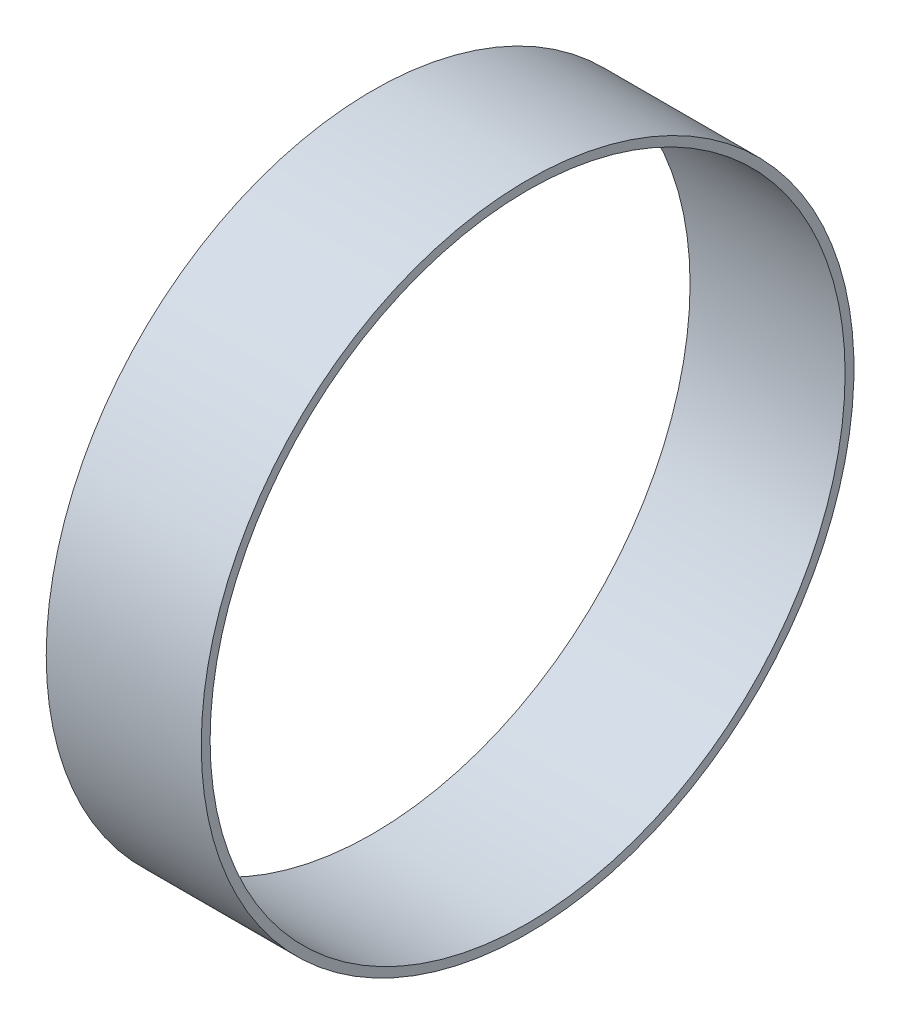
SolidWorks part; units mm, degrees
ref_plane "Plan1" through (0, 0, 0) normal (0, 0, 1) x (1, 0, 0)
ref_plane "Plan2" through (0, 0, 0) normal (0, 1, 0) x (1, 0, 0)
ref_plane "Plan3" through (0, 0, 0) normal (1, 0, 0) x (0, 0, -1)
sketch "Esquisse1" plane through (0, 0, 0) normal (0, 0, 1) x (1, 0, 0)
  line L0 (120.5, -36.84) -> (138, -36.84)
  line L1 (0, 0) -> (150, 0) construction
  line L2 (120.5, 27.25) -> (120.5, -27.25) construction
  line L3 (138, -27.25) -> (138, 27.25) construction
  dimension "D1" = 36.84
revolve "Base-Révol.-Mince" add sketch "Esquisse1" angle 360 about L1
